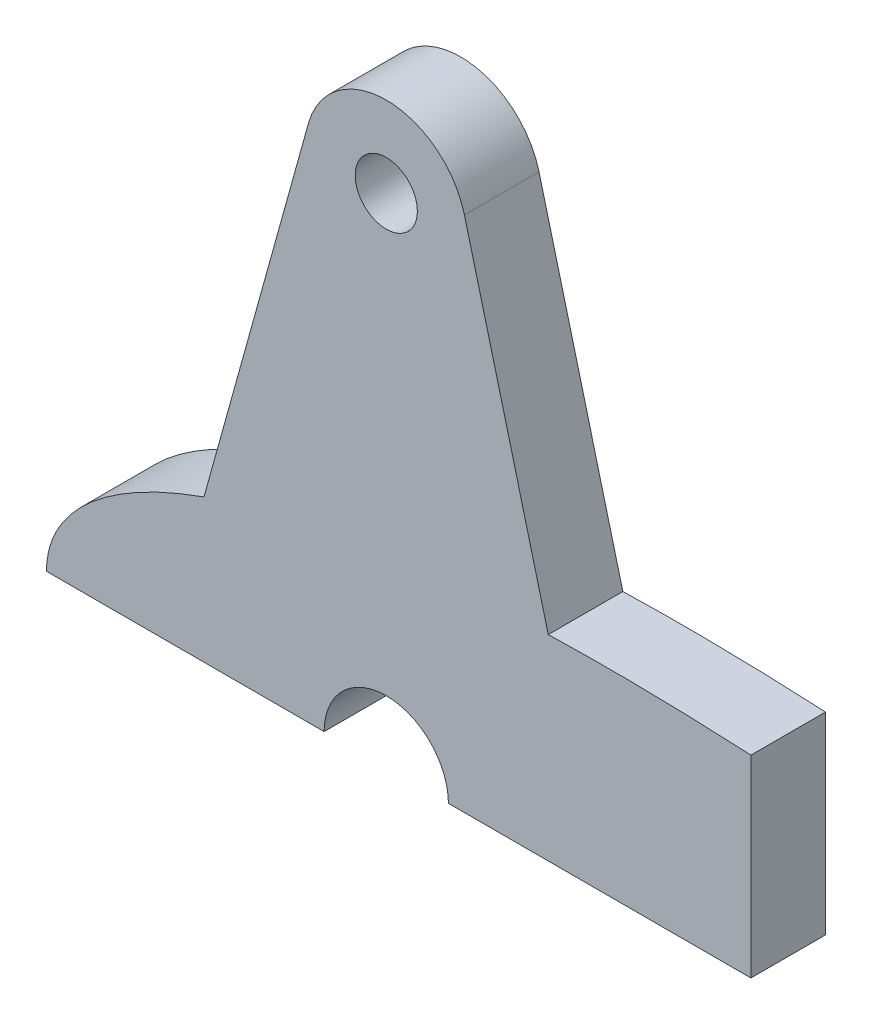
SolidWorks part; units mm, degrees
ref_plane "Front Plane" through (0, 0, 0) normal (0, 0, 1) x (1, 0, 0)
ref_plane "Top Plane" through (0, 0, 0) normal (0, 1, 0) x (1, 0, 0)
ref_plane "Right Plane" through (0, 0, 0) normal (1, 0, 0) x (0, 0, -1)
curve "Curve4"
  spline degree 3 poles (100, 0, 0) (99.8498, 0.0023, 0) (99.4759, 0.008, 0) (99.1023, 0.0238, 0) (98.8789, 0.0332, 0) knots 0 0 0 0 0.401829 1 1 1 1
curve "Curve5"
  spline degree 3 poles (99.3714, -0.0082, 0) (100.2526, 0, 0) (99.3714, 0.0082, 0) (98.8504, 0.035, 0) (97.904, 0.0811, 0) (96.8285, 0.1543, 0) (95.5159, 0.2583, 0) (94.013, 0.3972, 0) (92.313, 0.574, 0) (90.4281, 0.791, 0) (88.3655, 1.0495, 0) (86.1348, 1.3497, 0) (83.7456, 1.691, 0) (81.2082, 2.0715, 0) (78.5335, 2.4886, 0) (75.7326, 2.9386, 0) (72.8172, 3.4168, 0) (69.799, 3.9177, 0) (66.6904, 4.435, 0) (63.5039, 4.9616, 0) (60.2521, 5.4899, 0) (56.948, 6.0119, 0) (53.6049, 6.519, 0) (50.2363, 7.0024, 0) (46.8558, 7.4534, 0) (43.4774, 7.8632, 0) (40.1152, 8.2232, 0) (36.7837, 8.5249, 0) (33.4975, 8.7606, 0) (30.2716, 8.923, 0) (27.1211, 9.0055, 0) (24.0614, 9.0025, 0) (21.108, 8.909, 0) (18.277, 8.7213, 0) (15.5843, 8.4369, 0) (13.0466, 8.0543, 0) (10.6806, 7.5735, 0) (8.5039, 6.996, 0) (6.5349, 6.3253, 0) (4.7933, 5.5673, 0) (3.3001, 4.7321, 0) (2.0777, 3.8366, 0) (1.1467, 2.91, 0) (0.5165, 2.0014, 0) (0.165, 1.1816, 0) (0.0231, 0.524, 0) (-0.0093, 0, 0) (0.0231, -0.524, 0) (0.165, -1.1816, 0) (0.5165, -2.0014, 0) (1.1467, -2.91, 0) (2.0777, -3.8366, 0) (3.3001, -4.7321, 0) (4.7933, -5.5673, 0) (6.5349, -6.3253, 0) (8.5039, -6.996, 0) (10.6806, -7.5735, 0) (13.0466, -8.0543, 0) (15.5843, -8.4369, 0) (18.277, -8.7213, 0) (21.108, -8.909, 0) (24.0614, -9.0025, 0) (27.1211, -9.0055, 0) (30.2716, -8.923, 0) (33.4975, -8.7606, 0) (36.7837, -8.5249, 0) (40.1152, -8.2232, 0) (43.4774, -7.8632, 0) (46.8558, -7.4534, 0) (50.2363, -7.0024, 0) (53.6049, -6.519, 0) (56.948, -6.0119, 0) (60.2521, -5.4899, 0) (63.5039, -4.9616, 0) (66.6904, -4.435, 0) (69.799, -3.9177, 0) (72.8172, -3.4168, 0) (75.7326, -2.9386, 0) (78.5335, -2.4886, 0) (81.2082, -2.0715, 0) (83.7456, -1.691, 0) (86.1348, -1.3497, 0) (88.3655, -1.0495, 0) (90.4281, -0.791, 0) (92.313, -0.574, 0) (94.013, -0.3972, 0) (95.5159, -0.2583, 0) (96.8285, -0.1543, 0) (97.904, -0.0811, 0) (98.8504, -0.035, 0) (99.3714, -0.0082, 0) (100.2526, 0, 0) (99.3714, 0.0082, 0) knots -0.009667 -0.005395 -0.002168 0 0.002168 0.005395 0.009667 0.014967 0.021271 0.028553 0.036781 0.04592 0.055932 0.066773 0.078397 0.090755 0.103793 0.117456 0.131686 0.146422 0.1616 0.177156 0.193024 0.209135 0.225421 0.241812 0.258238 0.274629 0.290914 0.307025 0.322893 0.338448 0.353626 0.368361 0.38259 0.396253 0.40929 0.421647 0.43327 0.444109 0.454119 0.463255 0.471479 0.478755 0.485052 0.490344 0.49461 0.497833 0.5 0.502167 0.50539 0.509656 0.514948 0.521245 0.528521 0.536745 0.545881 0.555891 0.56673 0.578353 0.59071 0.603747 0.61741 0.631639 0.646374 0.661552 0.677107 0.692975 0.709086 0.725371 0.741762 0.758188 0.774579 0.790865 0.806976 0.822844 0.8384 0.853578 0.868314 0.882544 0.896207 0.909245 0.921603 0.933227 0.944068 0.95408 0.963219 0.971447 0.978729 0.985033 0.990333 0.994605 0.997832 1 1.002168 1.005395 1.009667 periodic
sketch "Sketch2" plane through (0, 0, 0) normal (0, 0, 1) x (1, 0, 0)
  line L0 (-849.2788, 0.0957) -> (49150.7212, 0.0957) construction
  line L1 (49.0354, -335.0363) -> (49.0354, 16331.6137) construction
  line L2 (9.5255, 0.0957) -> (14.1822, 0.0957)
  line L3 (35.9839, 4.3291) -> (40.2172, 4.3291)
  line L4 (35.9839, 4.3291) -> (35.9839, -4.1376)
  line L5 (35.9839, -4.1376) -> (40.2172, -4.1376)
  line L6 (40.2172, 4.3291) -> (40.2172, -4.1376)
  line L7 (35.9839, 4.3291) -> (40.2172, -4.1376) construction
  line L8 (35.9839, -4.1376) -> (40.2172, 4.3291) construction
  line L9 (61.3839, 3.2707) -> (65.6172, 3.2707)
  line L10 (61.3839, 3.2707) -> (61.3839, -3.0793)
  line L11 (61.3839, -3.0793) -> (65.6172, -3.0793)
  line L12 (65.6172, 3.2707) -> (65.6172, -3.0793)
  line L13 (61.3839, 3.2707) -> (65.6172, -3.0793) construction
  line L14 (61.3839, -3.0793) -> (65.6172, 3.2707) construction
  line L15 (20.5322, 0.0957) -> (35.9839, 0.0957)
  line L16 (40.2172, 0.0957) -> (61.3839, 0.0957)
  line L17 (65.6172, 0.0957) -> (103.8637, 0.0957)
  line L18 (25.6323, 10.1119) -> (21.3513, 26.5367)
  line L19 (17.3572, -999.9043) -> (17.3572, 49000.0957) construction
  line L20 (8.0452, 7.407) -> (13.3805, 26.6011)
  line L21 (0.0005, 0.0957) -> (9.5255, 0.0957)
  circle A0 centre (4.763, 0.0957) radius 4.7625
  circle A1 centre (17.3572, 0.0957) radius 3.175
  circle A2 centre (103.2287, 0.0957) radius 0.635 construction
  arc A3 (103.2287, 0.7307) -> (103.8637, 0.0957) centre (103.2287, 0.0957) cw
  arc A4 (103.8637, 0.0957) -> (103.2287, -0.5393) centre (103.2287, 0.0957) cw
  circle A5 centre (17.3572, 25.4957) radius 1.5875
  arc A6 (21.3513, 26.5367) -> (13.3805, 26.6011) centre (17.3572, 25.4957) ccw
  circle A8 centre (17.3572, 25.4957) radius 4.1275 construction
  spline S2 degree 3 poles (111.0579, 0.0866) (112.0427, 0.0957) (111.0579, 0.1048) (110.4756, 0.1348) (109.4179, 0.1863) (108.2159, 0.2682) (106.749, 0.3844) (105.0694, 0.5396) (103.1695, 0.7373) (101.0629, 0.9798) (98.7578, 1.2687) (96.2647, 1.6042) (93.5945, 1.9855) (90.7587, 2.4108) (87.7695, 2.877) (84.6392, 3.3799) (81.3809, 3.9143) (78.0079, 4.4741) (74.5337, 5.0522) (70.9724, 5.6408) (67.3382, 6.2313) (63.6456, 6.8146) (59.9094, 7.3813) (56.1446, 7.9216) (52.3665, 8.4257) (48.5908, 8.8837) (44.8332, 9.2859) (41.1099, 9.6231) (37.4373, 9.8866) (33.832, 10.0681) (30.311, 10.1603) (26.8915, 10.1569) (23.5909, 10.0524) (20.4269, 9.8427) (17.4176, 9.5248) (14.5814, 9.0972) (11.9371, 8.5598) (9.5045, 7.9145) (7.3039, 7.1649) (5.3575, 6.3177) (3.6887, 5.3843) (2.3226, 4.3835) (1.2821, 3.3479) (0.5777, 2.3324) (0.1849, 1.4163) (0.0263, 0.6814) (-0.0098, 0.0957) (0.0263, -0.4899) (0.1849, -1.2248) (0.5777, -2.141) (1.2821, -3.1565) (2.3226, -4.192) (3.6887, -5.1928) (5.3575, -6.1263) (7.3039, -6.9734) (9.5045, -7.723) (11.9371, -8.3684) (14.5814, -8.9058) (17.4176, -9.3333) (20.4269, -9.6512) (23.5909, -9.8609) (26.8915, -9.9654) (30.311, -9.9689) (33.832, -9.8766) (37.4373, -9.6951) (41.1099, -9.4317) (44.8332, -9.0945) (48.5908, -8.6922) (52.3665, -8.2342) (56.1446, -7.7302) (59.9094, -7.1899) (63.6456, -6.6231) (67.3382, -6.0398) (70.9724, -5.4493) (74.5337, -4.8608) (78.0079, -4.2827) (81.3809, -3.7229) (84.6392, -3.1885) (87.7695, -2.6856) (90.7587, -2.2194) (93.5945, -1.7941) (96.2647, -1.4127) (98.7578, -1.0772) (101.0629, -0.7883) (103.1695, -0.5458) (105.0694, -0.3482) (106.749, -0.1929) (108.2159, -0.0767) (109.4179, 0.0051) (110.4756, 0.0567) (111.0579, 0.0866) (112.0427, 0.0957) (111.0579, 0.1048) knots -0.009667 -0.005395 -0.002168 0 0.002168 0.005395 0.009667 0.014967 0.021271 0.028553 0.036781 0.04592 0.055932 0.066773 0.078397 0.090755 0.103793 0.117456 0.131686 0.146422 0.1616 0.177156 0.193024 0.209135 0.225421 0.241812 0.258238 0.274629 0.290914 0.307025 0.322893 0.338448 0.353626 0.368361 0.38259 0.396253 0.40929 0.421647 0.43327 0.444109 0.454119 0.463255 0.471479 0.478755 0.485052 0.490344 0.49461 0.497833 0.5 0.502167 0.50539 0.509656 0.514948 0.521245 0.528521 0.536745 0.545881 0.555891 0.56673 0.578353 0.59071 0.603747 0.61741 0.631639 0.646374 0.661552 0.677107 0.692975 0.709086 0.725371 0.741762 0.758188 0.774579 0.790865 0.806976 0.822844 0.8384 0.853578 0.868314 0.882544 0.896207 0.909245 0.921603 0.933227 0.944068 0.95408 0.963219 0.971447 0.978729 0.985033 0.990333 0.994605 0.997832 1 1.002168 1.005395 1.009667 only from (111.7604, 0.0957) to (111.7604, 0.0957)
  point P0 (0.0005, 0.0957)
  point P8 (49.0354, -5.9242)
  point P10 (49.0354, 6.4985)
  point P13 (27.9405, 0.0957)
  point P14 (38.1005, 0.0957)
  point P19 (63.5005, 0.0957)
  point P49 (22.8225, 27.1666)
  dimension "D2" = 9.525
  dimension "D1" = 6.35
  dimension "D11" = 1.27
  dimension "D12" = 3.175
  dimension "D3" = 27.94
  dimension "D4" = 10.5833
  dimension "D5" = 4.2333
  dimension "D6" = 8.4667
  dimension "D7" = 38.1
  dimension "D8" = 6.35
  dimension "D9" = 4.2333
  dimension "D10" = 25.4
  dimension "D13" = 25.4
  dimension "D14" = 2.54
extrude "Boss-Extrude1" add sketch "Sketch2" along normal blind 6.35
sketch "Sketch3" plane through (0, 0, 6.35) normal (0, 0, 1) x (1, 0, 0)
  line L0 (35.9839, 4.3291) -> (35.9839, 0.0957) construction
  line L1 (35.9839, 43.9682) -> (122.5042, 43.9682)
  line L2 (35.9839, 43.9682) -> (35.9839, -6.7846)
  line L3 (35.9839, -6.7846) -> (122.5042, -6.7846)
  line L4 (122.5042, 43.9682) -> (122.5042, -6.7846)
  line L5 (35.9839, 43.9682) -> (122.5042, -6.7846) construction
  line L6 (35.9839, -6.7846) -> (122.5042, 43.9682) construction
  point P0 (79.244, 18.5918)
extrude "Cut-Extrude1" cut sketch "Sketch3" against normal blind 22.86
scale "Scale1" scale about centroid uniform scaling yes scale factor 2
sketch "Sketch4" plane through (0, 0, 9.525) normal (0, 0, 1) x (1, 0, 0)
  line L1 (-123.5056, 184.9525) -> (149.2238, 184.9525)
  line L2 (-123.5056, 184.9525) -> (-123.5056, -169.8794)
  line L3 (-123.5056, -169.8794) -> (149.2238, -169.8794)
  line L4 (149.2238, 184.9525) -> (149.2238, -169.8794)
  line L5 (-123.5056, 184.9525) -> (149.2238, -169.8794) construction
  line L6 (-123.5056, -169.8794) -> (149.2238, 184.9525) construction
  point P0 (12.8591, 7.5365)
extrude "Cut-Extrude2" cut sketch "Sketch4" against normal blind 5.08
equation "\"D5@Sketch2\"=.5/3"
equation "\"D6@Sketch2\"=1/3"
equation "\"D7@Sketch2\"=4.5/3"
equation "\"D9@Sketch2\"=.5/3"
equation "\"D1@Sketch2\"=0.5/2"
equation "\"D12@Sketch2\"=0.25/2"
